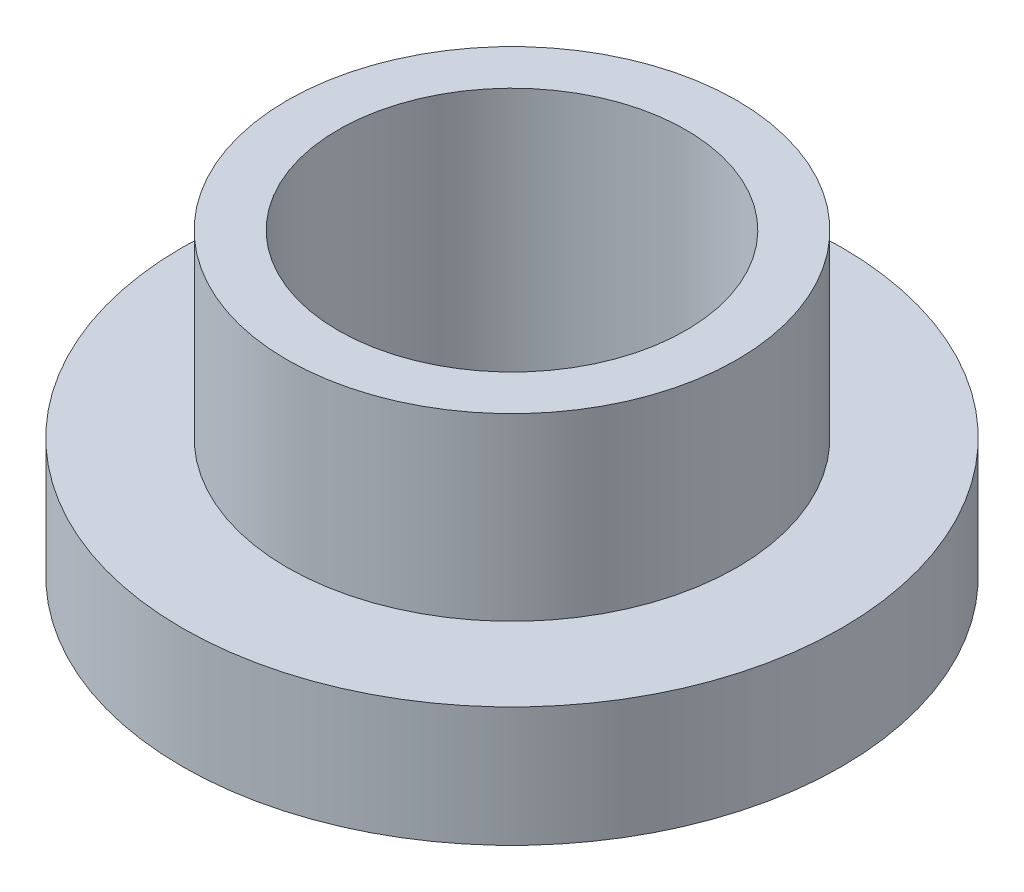
SolidWorks part; units mm, degrees
ref_plane "Plan de face" through (0, 0, 0) normal (0, 0, 1) x (1, 0, 0)
ref_plane "Plan de dessus" through (0, 0, 0) normal (0, 1, 0) x (1, 0, 0)
ref_plane "Plan de droite" through (0, 0, 0) normal (1, 0, 0) x (0, 0, -1)
sketch "Esquisse1" plane through (0, 0, 0) normal (0, 1, 0) x (1, 0, 0)
  circle A0 centre (0, 0) radius 2.9
  circle A1 centre (0, 0) radius 5.5
  dimension "D1" = 11
  dimension "D2" = 5.8
extrude "Boss.-Extru.1" add sketch "Esquisse1" along normal blind 2
sketch "Esquisse2" plane through (0, 2, 0) normal (0, 1, 0) x (1, 0, 0)
  circle A0 centre (0, 0) radius 2.9
  circle A1 centre (0, 0) radius 3.75
  dimension "D1" = 5.8
  dimension "D2" = 7.5
extrude "Boss.-Extru.2" add sketch "Esquisse2" along normal blind 3
